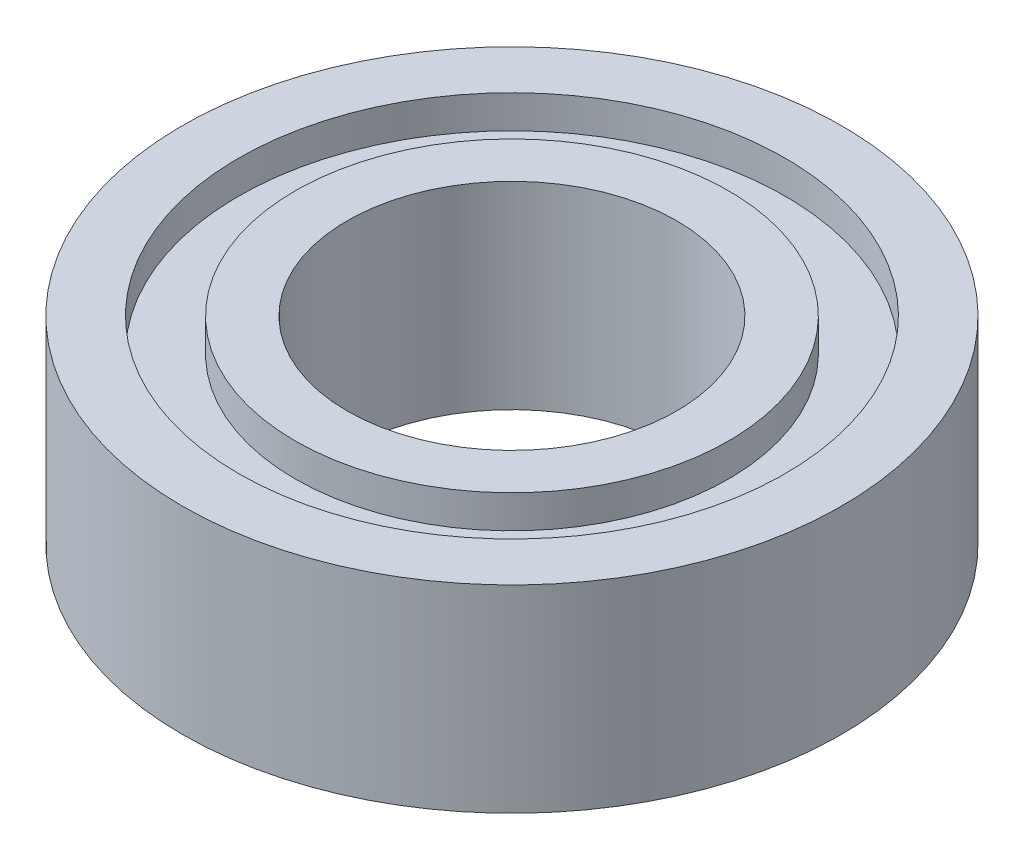
SolidWorks part; units mm, degrees
ref_plane "Front Plane" through (0, 0, 0) normal (0, 0, 1) x (1, 0, 0)
ref_plane "Top Plane" through (0, 0, 0) normal (0, 1, 0) x (1, 0, 0)
ref_plane "Right Plane" through (0, 0, 0) normal (1, 0, 0) x (0, 0, -1)
sketch "Sketch1" plane through (0, 0, 0) normal (0, 1, 0) x (1, 0, 0)
  circle A0 centre (0, 0) radius 10
  circle A1 centre (0, 0) radius 5
  dimension "D1" = 10
  dimension "D2" = 20
extrude "Boss-Extrude1" add sketch "Sketch1" along normal mid plane 6
sketch "Sketch2" plane through (0, 3, 0) normal (0, 1, 0) x (1, 0, 0)
  circle A0 centre (0, 0) radius 6.5748
  circle A1 centre (0, 0) radius 8.2927
extrude "Cut-Extrude1" cut sketch "Sketch2" against normal blind 1
mirror "Mirror1" about plane through (0, 0, 0) normal (0, 1, 0) of "Cut-Extrude1"
